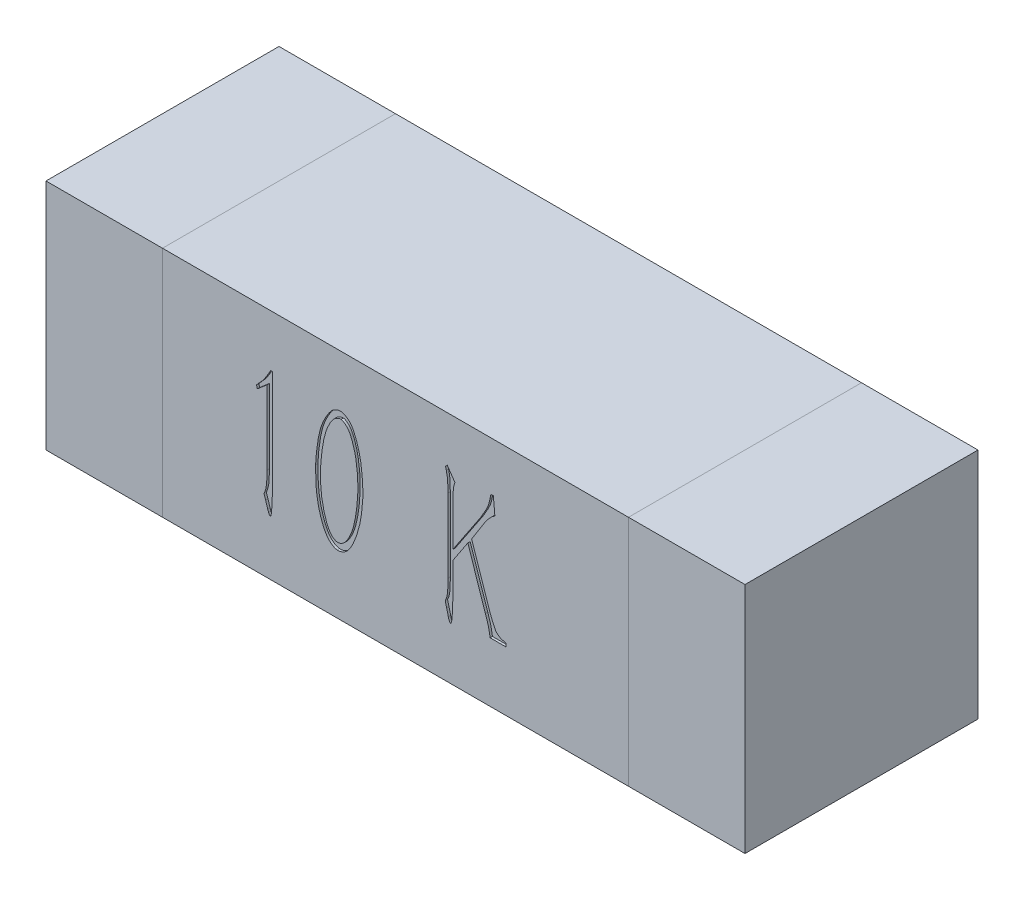
SolidWorks part; units mm, degrees
ref_plane "前视基准面" through (0, 0, 0) normal (0, 0, 1) x (1, 0, 0)
ref_plane "上视基准面" through (0, 0, 0) normal (0, 1, 0) x (1, 0, 0)
ref_plane "右视基准面" through (0, 0, 0) normal (1, 0, 0) x (0, 0, -1)
sketch "草图1" plane through (0, 0, 0) normal (0, 0, 1) x (1, 0, 0)
  line L1 (-1, 0.5) -> (1, 0.5)
  line L2 (-1, 0.5) -> (-1, -0.5)
  line L3 (-1, -0.5) -> (1, -0.5)
  line L4 (1, 0.5) -> (1, -0.5)
  line L5 (-1, 0.5) -> (1, -0.5) construction
  line L6 (-1, -0.5) -> (1, 0.5) construction
  point P0 (0, 0)
extrude "凸台-拉伸1" add sketch "草图1" along normal blind 1
sketch "草图2" plane through (0, 0, 0) normal (0, 0, -1) x (-1, 0, 0)
  line L1 (1, 0.5) -> (1.5, 0.5)
  line L2 (1, 0.5) -> (1, -0.5)
  line L3 (1, -0.5) -> (1.5, -0.5)
  line L4 (1.5, 0.5) -> (1.5, -0.5)
  line L5 (-1, 0.5) -> (-1.5, 0.5)
  line L6 (-1, 0.5) -> (-1, -0.5)
  line L7 (-1, -0.5) -> (-1.5, -0.5)
  line L8 (-1.5, 0.5) -> (-1.5, -0.5)
extrude "凸台-拉伸2" add sketch "草图2" against normal blind 1 separate body
sketch "草图4" plane through (0, 0, 1) normal (0, 0, 1) x (1, 0, 0)
  line L0 (-0.68, -0.2928) -> (0.6895, -0.2928) construction
  text T0 "10 K" font "汉仪长仿宋体" height in points 2
extrude "切除-拉伸1" cut sketch "草图4" against normal blind 0.01
